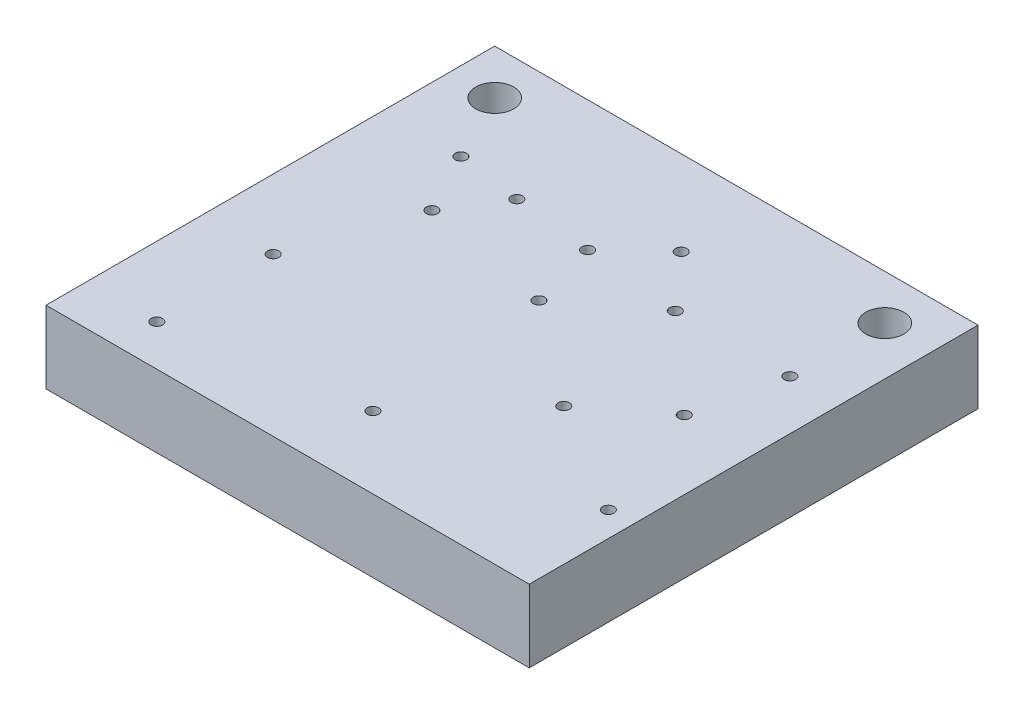
SolidWorks part; units mm, degrees
ref_plane "Front Plane" through (0, 0, 0) normal (0, 0, 1) x (1, 0, 0)
ref_plane "Top Plane" through (0, 0, 0) normal (0, 1, 0) x (1, 0, 0)
ref_plane "Right Plane" through (0, 0, 0) normal (1, 0, 0) x (0, 0, -1)
sketch "Sketch2" plane through (0, 0, 0) normal (0, 1, 0) x (1, 0, 0)
  line L0 (13, -13) -> (126, -13) construction
  line L1 (0, -130) -> (140, -130)
  line L2 (0, -130) -> (0, 0)
  line L3 (0, 0) -> (140, 0)
  line L4 (140, -130) -> (140, 0)
  circle A0 centre (13, -13) radius 5.5
  circle A1 centre (126, -13) radius 5.5
  circle A2 centre (78.6, -24.6) radius 1.65
  circle A3 centre (120, -65.1) radius 1.65
  circle A4 centre (73.9, -109.2) radius 1.65
  circle A5 centre (32.1, -50.3) radius 1.65
  circle A6 centre (22.8, -32.6) radius 1.65
  circle A7 centre (41.6, -35.2) radius 1.65
  circle A8 centre (64.6, -37.7) radius 1.65
  circle A9 centre (92.6, -40.3) radius 1.65
  circle A10 centre (125.6, -40.1) radius 1.65
  circle A11 centre (20.1, -84.3) radius 1.65
  circle A12 centre (20.2, -118.1) radius 1.65
  circle A13 centre (70.2, -57.4) radius 1.65
  circle A14 centre (100.3, -80.3) radius 1.65
  circle A15 centre (132.8, -99.9) radius 1.65
  dimension "D3" = 113
  dimension "D4" = 11
  dimension "D7" = 3.3
  dimension "D16" = 22.8
  dimension "D18" = 41.6
  dimension "D20" = 37.7
  dimension "D22" = 92.6
  dimension "D24" = 125.6
  dimension "D26" = 20.1
  dimension "D28" = 118.1
  dimension "D30" = 70.2
  dimension "D32" = 100.3
  dimension "D34" = 132.8
  dimension "D1" = 140
  dimension "D2" = 130
  dimension "D5" = 13
  dimension "D6" = 13
  dimension "D8" = 24.6
  dimension "D9" = 78.6
  dimension "D10" = 65.1
  dimension "D11" = 120
  dimension "D12" = 109.2
  dimension "D13" = 73.9
  dimension "D14" = 32.1
  dimension "D15" = 50.3
  dimension "D17" = 32.6
  dimension "D19" = 35.2
  dimension "D21" = 64.6
  dimension "D23" = 40.3
  dimension "D25" = 40.1
  dimension "D27" = 84.3
  dimension "D29" = 20.2
  dimension "D31" = 57.4
  dimension "D33" = 80.3
  dimension "D35" = 99.9
extrude "Boss-Extrude1" add sketch "Sketch2" along normal blind 21
